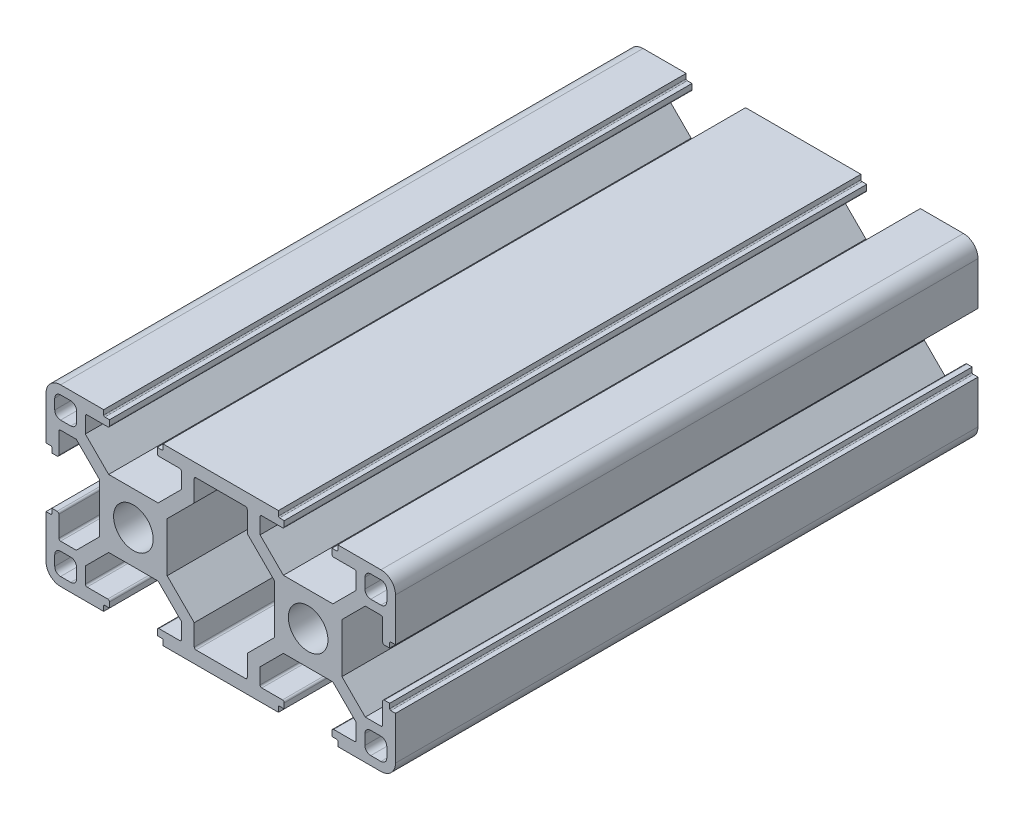
SolidWorks part; units mm, degrees
ref_plane "前视基准面" through (0, 0, 0) normal (0, 0, 1) x (1, 0, 0)
ref_plane "上视基准面" through (0, 0, 0) normal (0, 1, 0) x (1, 0, 0)
ref_plane "右视基准面" through (0, 0, 0) normal (1, 0, 0) x (0, 0, -1)
sketch "草图1" plane through (0, 0, 0) normal (0, 0, 1) x (1, 0, 0)
  line L0 (-35.8468, -15.0561) -> (-35.8468, -16.8061)
  line L1 (-36.8468, -17.8061) -> (-38.5968, -17.8061)
  line L2 (-39.5968, -16.8061) -> (-39.5968, -15.0561)
  line L3 (-38.5968, -14.0561) -> (-36.8468, -14.0561)
  line L4 (-36.8468, 5.4439) -> (-38.5968, 5.4439)
  line L5 (-39.5968, 6.4439) -> (-39.5968, 8.1939)
  line L6 (-38.5968, 9.1939) -> (-36.8468, 9.1939)
  line L7 (-35.8468, 8.1939) -> (-35.8468, 6.4439)
  line L8 (-15.6468, -13.2005) -> (-20.2968, -8.5505)
  line L9 (-20.2968, -8.5505) -> (-20.2968, -0.0618)
  line L10 (-20.2968, -0.0618) -> (-15.6468, 4.5882)
  line L11 (-13.5968, 10.6939) -> (-20.9968, 10.6939)
  line L12 (-20.9968, 10.6939) -> (-20.9968, 9.8939)
  line L13 (-21.1968, 9.6939) -> (-21.9968, 9.6939)
  line L14 (-21.9968, 9.6939) -> (-21.9968, 8.7939)
  line L15 (-21.6968, 8.4939) -> (-18.1468, 8.4939)
  line L16 (-17.8468, 8.1939) -> (-17.8468, 5.4995)
  line L17 (-17.8468, 5.4995) -> (-21.8524, 1.4939)
  line L18 (-21.8524, 1.4939) -> (-30.3412, 1.4939)
  line L19 (-30.3412, 1.4939) -> (-34.3468, 5.4995)
  line L20 (-34.3468, 5.4995) -> (-34.3468, 8.1939)
  line L21 (-34.0468, 8.4939) -> (-30.4968, 8.4939)
  line L22 (-30.1968, 8.7939) -> (-30.1968, 9.6939)
  line L23 (-30.1968, 9.6939) -> (-30.9968, 9.6939)
  line L24 (-31.1968, 9.8939) -> (-31.1968, 10.6939)
  line L25 (-31.1968, 10.6939) -> (-38.5968, 10.6939)
  line L26 (-41.0968, 8.1939) -> (-41.0968, 0.7939)
  line L27 (-41.0968, 0.7939) -> (-40.2968, 0.7939)
  line L28 (-40.0968, 0.5939) -> (-40.0968, -0.2061)
  line L29 (-40.0968, -0.2061) -> (-39.1968, -0.2061)
  line L30 (-38.8968, 0.0939) -> (-38.8968, 3.6439)
  line L31 (-38.5968, 3.9439) -> (-35.9024, 3.9439)
  line L32 (-35.9024, 3.9439) -> (-31.8968, -0.0618)
  line L33 (-31.8968, -0.0618) -> (-31.8968, -8.5505)
  line L34 (-31.8968, -8.5505) -> (-35.9024, -12.5561)
  line L35 (-35.9024, -12.5561) -> (-38.5968, -12.5561)
  line L36 (-38.8968, -12.2561) -> (-38.8968, -8.7061)
  line L37 (-39.1968, -8.4061) -> (-40.0968, -8.4061)
  line L38 (-40.0968, -8.4061) -> (-40.0968, -9.2061)
  line L39 (-40.2968, -9.4061) -> (-41.0968, -9.4061)
  line L40 (-41.0968, -9.4061) -> (-41.0968, -16.8061)
  line L41 (-38.5968, -19.3061) -> (-31.1968, -19.3061)
  line L42 (-31.1968, -19.3061) -> (-31.1968, -18.5061)
  line L43 (-30.9968, -18.3061) -> (-30.1968, -18.3061)
  line L44 (-30.1968, -18.3061) -> (-30.1968, -17.4061)
  line L45 (-30.4968, -17.1061) -> (-34.0468, -17.1061)
  line L46 (-34.3468, -16.8061) -> (-34.3468, -14.1118)
  line L47 (-34.3468, -14.1118) -> (-30.3412, -10.1061)
  line L48 (-30.3412, -10.1061) -> (-21.8524, -10.1061)
  line L49 (-21.8524, -10.1061) -> (-17.8468, -14.1118)
  line L50 (-17.8468, -14.1118) -> (-17.8468, -16.8061)
  line L51 (-18.1468, -17.1061) -> (-21.6968, -17.1061)
  line L52 (-21.9968, -17.4061) -> (-21.9968, -18.3061)
  line L53 (-21.9968, -18.3061) -> (-21.1968, -18.3061)
  line L54 (-20.9968, -18.5061) -> (-20.9968, -19.3061)
  line L55 (-20.9968, -19.3061) -> (-13.5968, -19.3061)
  line L56 (14.6532, -14.0561) -> (16.4032, -14.0561)
  line L57 (17.4032, -15.0561) -> (17.4032, -16.8061)
  line L58 (16.4032, -17.8061) -> (14.6532, -17.8061)
  line L59 (13.6532, -16.8061) -> (13.6532, -15.0561)
  line L60 (13.6532, 6.4439) -> (13.6532, 8.1939)
  line L61 (14.6532, 9.1939) -> (16.4032, 9.1939)
  line L62 (17.4032, 8.1939) -> (17.4032, 6.4439)
  line L63 (16.4032, 5.4439) -> (14.6532, 5.4439)
  line L64 (-8.5968, -19.3061) -> (-1.1968, -19.3061)
  line L65 (-1.1968, -19.3061) -> (-1.1968, -18.5061)
  line L66 (-0.9968, -18.3061) -> (-0.1968, -18.3061)
  line L67 (-0.1968, -18.3061) -> (-0.1968, -17.4061)
  line L68 (-0.4968, -17.1061) -> (-4.0468, -17.1061)
  line L69 (-4.3468, -16.8061) -> (-4.3468, -14.1118)
  line L70 (-4.3468, -14.1118) -> (-0.3412, -10.1061)
  line L71 (-0.3412, -10.1061) -> (8.1476, -10.1061)
  line L72 (8.1476, -10.1061) -> (12.1532, -14.1118)
  line L73 (12.1532, -14.1118) -> (12.1532, -16.8061)
  line L74 (11.8532, -17.1061) -> (8.3032, -17.1061)
  line L75 (8.0032, -17.4061) -> (8.0032, -18.3061)
  line L76 (8.0032, -18.3061) -> (8.8032, -18.3061)
  line L77 (9.0032, -18.5061) -> (9.0032, -19.3061)
  line L78 (9.0032, -19.3061) -> (16.4032, -19.3061)
  line L79 (18.9032, -16.8061) -> (18.9032, -9.4061)
  line L80 (18.9032, -9.4061) -> (18.1032, -9.4061)
  line L81 (17.9032, -9.2061) -> (17.9032, -8.4061)
  line L82 (17.9032, -8.4061) -> (17.0032, -8.4061)
  line L83 (16.7032, -8.7061) -> (16.7032, -12.2561)
  line L84 (16.4032, -12.5561) -> (13.7088, -12.5561)
  line L85 (13.7088, -12.5561) -> (9.7032, -8.5505)
  line L86 (9.7032, -8.5505) -> (9.7032, -0.0618)
  line L87 (9.7032, -0.0618) -> (13.7088, 3.9439)
  line L88 (13.7088, 3.9439) -> (16.4032, 3.9439)
  line L89 (16.7032, 3.6439) -> (16.7032, 0.0939)
  line L90 (17.0032, -0.2061) -> (17.9032, -0.2061)
  line L91 (17.9032, -0.2061) -> (17.9032, 0.5939)
  line L92 (18.1032, 0.7939) -> (18.9032, 0.7939)
  line L93 (18.9032, 0.7939) -> (18.9032, 8.1939)
  line L94 (16.4032, 10.6939) -> (9.0032, 10.6939)
  line L95 (9.0032, 10.6939) -> (9.0032, 9.8939)
  line L96 (8.8032, 9.6939) -> (8.0032, 9.6939)
  line L97 (8.0032, 9.6939) -> (8.0032, 8.7939)
  line L98 (8.3032, 8.4939) -> (11.8532, 8.4939)
  line L99 (12.1532, 8.1939) -> (12.1532, 5.4995)
  line L100 (12.1532, 5.4995) -> (8.1476, 1.4939)
  line L101 (8.1476, 1.4939) -> (-0.3412, 1.4939)
  line L102 (-0.3412, 1.4939) -> (-4.3468, 5.4995)
  line L103 (-4.3468, 5.4995) -> (-4.3468, 8.1939)
  line L104 (-4.0468, 8.4939) -> (-0.4968, 8.4939)
  line L105 (-0.1968, 8.7939) -> (-0.1968, 9.6939)
  line L106 (-0.1968, 9.6939) -> (-0.9968, 9.6939)
  line L107 (-1.1968, 9.8939) -> (-1.1968, 10.6939)
  line L108 (-1.1968, 10.6939) -> (-8.5968, 10.6939)
  line L109 (-6.5468, 4.5882) -> (-1.8968, -0.0618)
  line L110 (-1.8968, -0.0618) -> (-1.8968, -8.5505)
  line L111 (-1.8968, -8.5505) -> (-6.5468, -13.2005)
  line L112 (-13.5968, 10.6939) -> (-8.5968, 10.6939)
  line L113 (-13.5968, -19.3061) -> (-8.5968, -19.3061)
  line L114 (-6.5468, -16.8061) -> (-6.5468, -13.2005)
  line L115 (-15.6468, -16.8061) -> (-15.6468, -13.2005)
  line L117 (-15.3468, -17.1061) -> (-6.8468, -17.1061)
  line L119 (-15.3468, 8.4939) -> (-6.8468, 8.4939)
  line L120 (-15.6468, 8.1939) -> (-15.6468, 4.5882)
  line L121 (-6.5468, 8.1939) -> (-6.5468, 4.5882)
  arc A0 (-36.8468, -17.8061) -> (-35.8468, -16.8061) centre (-36.8468, -16.8061) ccw
  arc A1 (-39.5968, -16.8061) -> (-38.5968, -17.8061) centre (-38.5968, -16.8061) ccw
  arc A2 (-38.5968, -14.0561) -> (-39.5968, -15.0561) centre (-38.5968, -15.0561) ccw
  arc A3 (-35.8468, -15.0561) -> (-36.8468, -14.0561) centre (-36.8468, -15.0561) ccw
  arc A4 (-39.5968, 6.4439) -> (-38.5968, 5.4439) centre (-38.5968, 6.4439) ccw
  arc A5 (-38.5968, 9.1939) -> (-39.5968, 8.1939) centre (-38.5968, 8.1939) ccw
  arc A6 (-35.8468, 8.1939) -> (-36.8468, 9.1939) centre (-36.8468, 8.1939) ccw
  arc A7 (-36.8468, 5.4439) -> (-35.8468, 6.4439) centre (-36.8468, 6.4439) ccw
  arc A9 (-21.1968, 9.6939) -> (-20.9968, 9.8939) centre (-21.1968, 9.8939) ccw
  arc A10 (-21.9968, 8.7939) -> (-21.6968, 8.4939) centre (-21.6968, 8.7939) ccw
  arc A11 (-17.8468, 8.1939) -> (-18.1468, 8.4939) centre (-18.1468, 8.1939) ccw
  arc A12 (-34.0468, 8.4939) -> (-34.3468, 8.1939) centre (-34.0468, 8.1939) ccw
  arc A13 (-30.4968, 8.4939) -> (-30.1968, 8.7939) centre (-30.4968, 8.7939) ccw
  arc A14 (-31.1968, 9.8939) -> (-30.9968, 9.6939) centre (-30.9968, 9.8939) ccw
  arc A15 (-38.5968, 10.6939) -> (-41.0968, 8.1939) centre (-38.5968, 8.1939) ccw
  arc A16 (-40.0968, 0.5939) -> (-40.2968, 0.7939) centre (-40.2968, 0.5939) ccw
  arc A17 (-39.1968, -0.2061) -> (-38.8968, 0.0939) centre (-39.1968, 0.0939) ccw
  arc A18 (-38.5968, 3.9439) -> (-38.8968, 3.6439) centre (-38.5968, 3.6439) ccw
  arc A19 (-38.8968, -12.2561) -> (-38.5968, -12.5561) centre (-38.5968, -12.2561) ccw
  arc A20 (-38.8968, -8.7061) -> (-39.1968, -8.4061) centre (-39.1968, -8.7061) ccw
  arc A21 (-40.2968, -9.4061) -> (-40.0968, -9.2061) centre (-40.2968, -9.2061) ccw
  arc A22 (-41.0968, -16.8061) -> (-38.5968, -19.3061) centre (-38.5968, -16.8061) ccw
  arc A23 (-30.9968, -18.3061) -> (-31.1968, -18.5061) centre (-30.9968, -18.5061) ccw
  arc A24 (-30.1968, -17.4061) -> (-30.4968, -17.1061) centre (-30.4968, -17.4061) ccw
  arc A25 (-34.3468, -16.8061) -> (-34.0468, -17.1061) centre (-34.0468, -16.8061) ccw
  arc A26 (-18.1468, -17.1061) -> (-17.8468, -16.8061) centre (-18.1468, -16.8061) ccw
  arc A27 (-21.6968, -17.1061) -> (-21.9968, -17.4061) centre (-21.6968, -17.4061) ccw
  arc A28 (-20.9968, -18.5061) -> (-21.1968, -18.3061) centre (-21.1968, -18.5061) ccw
  arc A29 (17.4032, -15.0561) -> (16.4032, -14.0561) centre (16.4032, -15.0561) ccw
  arc A30 (16.4032, -17.8061) -> (17.4032, -16.8061) centre (16.4032, -16.8061) ccw
  arc A31 (13.6532, -16.8061) -> (14.6532, -17.8061) centre (14.6532, -16.8061) ccw
  arc A32 (14.6532, -14.0561) -> (13.6532, -15.0561) centre (14.6532, -15.0561) ccw
  arc A33 (14.6532, 9.1939) -> (13.6532, 8.1939) centre (14.6532, 8.1939) ccw
  arc A34 (17.4032, 8.1939) -> (16.4032, 9.1939) centre (16.4032, 8.1939) ccw
  arc A35 (16.4032, 5.4439) -> (17.4032, 6.4439) centre (16.4032, 6.4439) ccw
  arc A36 (13.6532, 6.4439) -> (14.6532, 5.4439) centre (14.6532, 6.4439) ccw
  arc A38 (-0.9968, -18.3061) -> (-1.1968, -18.5061) centre (-0.9968, -18.5061) ccw
  arc A39 (-0.1968, -17.4061) -> (-0.4968, -17.1061) centre (-0.4968, -17.4061) ccw
  arc A40 (-4.3468, -16.8061) -> (-4.0468, -17.1061) centre (-4.0468, -16.8061) ccw
  arc A41 (11.8532, -17.1061) -> (12.1532, -16.8061) centre (11.8532, -16.8061) ccw
  arc A42 (8.3032, -17.1061) -> (8.0032, -17.4061) centre (8.3032, -17.4061) ccw
  arc A43 (9.0032, -18.5061) -> (8.8032, -18.3061) centre (8.8032, -18.5061) ccw
  arc A44 (16.4032, -19.3061) -> (18.9032, -16.8061) centre (16.4032, -16.8061) ccw
  arc A45 (17.9032, -9.2061) -> (18.1032, -9.4061) centre (18.1032, -9.2061) ccw
  arc A46 (17.0032, -8.4061) -> (16.7032, -8.7061) centre (17.0032, -8.7061) ccw
  arc A47 (16.4032, -12.5561) -> (16.7032, -12.2561) centre (16.4032, -12.2561) ccw
  arc A48 (16.7032, 3.6439) -> (16.4032, 3.9439) centre (16.4032, 3.6439) ccw
  arc A49 (16.7032, 0.0939) -> (17.0032, -0.2061) centre (17.0032, 0.0939) ccw
  arc A50 (18.1032, 0.7939) -> (17.9032, 0.5939) centre (18.1032, 0.5939) ccw
  arc A51 (18.9032, 8.1939) -> (16.4032, 10.6939) centre (16.4032, 8.1939) ccw
  arc A52 (8.8032, 9.6939) -> (9.0032, 9.8939) centre (8.8032, 9.8939) ccw
  arc A53 (8.0032, 8.7939) -> (8.3032, 8.4939) centre (8.3032, 8.7939) ccw
  arc A54 (12.1532, 8.1939) -> (11.8532, 8.4939) centre (11.8532, 8.1939) ccw
  arc A55 (-4.0468, 8.4939) -> (-4.3468, 8.1939) centre (-4.0468, 8.1939) ccw
  arc A56 (-0.4968, 8.4939) -> (-0.1968, 8.7939) centre (-0.4968, 8.7939) ccw
  arc A57 (-1.1968, 9.8939) -> (-0.9968, 9.6939) centre (-0.9968, 9.8939) ccw
  arc A58 (-15.6468, -16.8061) -> (-15.3468, -17.1061) centre (-15.3468, -16.8061) ccw
  arc A59 (-6.8468, -17.1061) -> (-6.5468, -16.8061) centre (-6.8468, -16.8061) ccw
  arc A60 (-15.3468, 8.4939) -> (-15.6468, 8.1939) centre (-15.3468, 8.1939) ccw
  arc A61 (-6.5468, 8.1939) -> (-6.8468, 8.4939) centre (-6.8468, 8.1939) ccw
  circle A70 centre (3.9032, -4.3061) radius 3.4
  circle A83 centre (-26.0968, -4.3061) radius 3.4
extrude "凸台-拉伸1" add sketch "草图1" along normal blind 100
